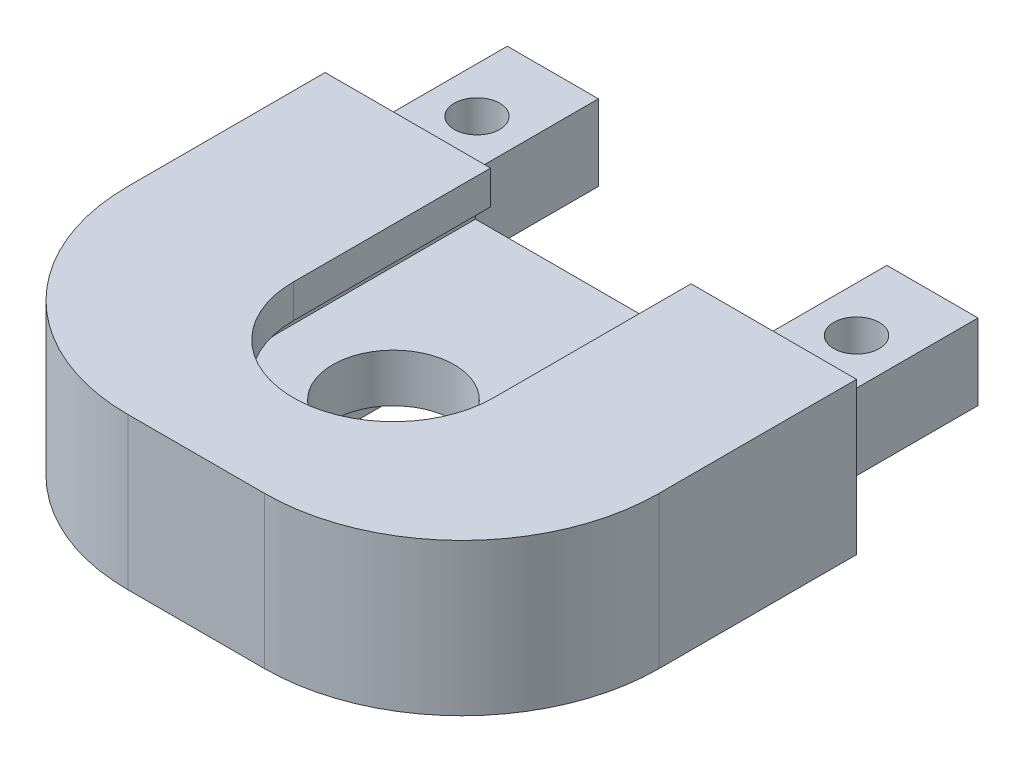
SolidWorks part; units mm, degrees
ref_plane "Front Plane" through (0, 0, 0) normal (0, 0, 1) x (1, 0, 0)
ref_plane "Top Plane" through (0, 0, 0) normal (0, 1, 0) x (1, 0, 0)
ref_plane "Right Plane" through (0, 0, 0) normal (1, 0, 0) x (0, 0, -1)
sketch "Sketch1" plane through (0, 0, 0) normal (0, 1, 0) x (1, 0, 0)
  line L0 (0, 0) -> (6, 0)
  line L1 (6, 0) -> (6, -10)
  line L2 (6, -10) -> (25, -10)
  line L3 (25, -10) -> (25, 0)
  line L4 (25, 0) -> (31, 0)
  line L5 (31, 0) -> (31, -10)
  line L7 (0, -10) -> (0, 0)
  line L8 (0, -10) -> (-2, -10)
  line L11 (33, -36) -> (33, -10)
  line L12 (33, -10) -> (31, -10)
  line L13 (3, 0) -> (3, -5) construction
  line L14 (15.5, -10) -> (15.5, 0) construction
  line L15 (33, -36) -> (-2, -36)
  line L16 (-2, -36) -> (-2, -10)
  circle A0 centre (3, -5) radius 1.5
  circle A1 centre (28, -5) radius 1.5
  dimension "D9" = 3
  dimension "D1" = 36
  dimension "D2" = 35
  dimension "D3" = 10
  dimension "D4" = 6
  dimension "D5" = 2
  dimension "D6" = 6
  dimension "D7" = 2
  dimension "D8" = 5
extrude "Boss-Extrude1" add sketch "Sketch1" along normal blind 5
sketch "Sketch2" plane through (0, 0, 36) normal (0, 0, 1) x (1, 0, 0)
  line L0 (-2, 5) -> (-2, 7.5)
  line L1 (-2, 7.5) -> (33, 7.5)
  line L2 (33, 7.5) -> (33, 5)
  line L3 (33, 5) -> (-2, 5)
  line L4 (-2, 0) -> (33, 0)
  line L5 (33, 0) -> (33, -2.5)
  line L6 (33, -2.5) -> (-2, -2.5)
  line L7 (-2, -2.5) -> (-2, 0)
  dimension "D1" = 10
extrude "Boss-Extrude2" add sketch "Sketch2" against normal up to surface (26 mm away) up to face at (15.5, 2.5, 10)
fillet "Fillet1" radius 13 2 edges at (33, 2.5, 36) (-2, 2.5, 36)
ref_plane "Plane1" through (0, 2.5, 0) normal (0, -1, 0) x (-1, 0, 0)
sketch "Sketch3" plane through (0, 0, 10) normal (0, 0, -1) x (-1, 0, 0)
  line L0 (-22.1, 7.5) -> (-22.1, 5.2875)
  line L1 (2, 7.5) -> (-33, 7.5) construction
  line L2 (-22.1, 5.2875) -> (-23.1, 5.2875)
  line L3 (-23.1, 5.2875) -> (-23.1, 4.0875)
  line L4 (-23.1, 4.0875) -> (-15.5, 4.0875)
  line L5 (-15.5, 4.0875) -> (-7.9, 4.0875)
  line L6 (-7.9, 4.0875) -> (-7.9, 5.2875)
  line L7 (-7.9, 5.2875) -> (-8.9, 5.2875)
  line L8 (-8.9, 5.2875) -> (-8.9, 7.5)
  line L9 (-8.9, 7.5) -> (-22.1, 7.5)
  line L10 (-25, 2.5) -> (-6, 2.5) construction
  line L11 (-25, 5) -> (-25, 0) construction
  line L12 (-6, 5) -> (-6, 0) construction
  line L13 (-15.5, 2.5) -> (-15.5, 4.0875) construction
  dimension "D1" = 1.2
  dimension "D2" = 3.4125
  dimension "D3" = 13.2
  dimension "D4" = 15.2
extrude "Cut-Extrude1" cut sketch "Sketch3" against normal blind 13 and the other way through all
sketch "Sketch4" plane through (0, 4.0875, 0) normal (0, 1, 0) x (1, 0, 0)
  line L0 (8.9, -23) -> (22.1, -23) construction
  circle A0 centre (15.5, -23) radius 7.6
  dimension "D1" = 15.2
extrude "Cut-Extrude2" cut sketch "Sketch4" along normal up to surface (1.2 mm away) up to face at (8.4, 5.2875, 16.5)
sketch "Sketch5" plane through (0, 4.0875, 0) normal (0, 1, 0) x (1, 0, 0)
  line L0 (8.9, -23) -> (22.1, -23) construction
  circle A0 centre (15.5, -23) radius 6.6
  dimension "D1" = 13.2
extrude "Cut-Extrude3" cut sketch "Sketch5" along normal through all
mirror "Mirror1" about plane through (0, 2.5, 0) normal (0, -1, 0) of "Cut-Extrude1"
sketch "Sketch6" plane through (0, 0.9125, 0) normal (0, -1, 0) x (1, 0, 0)
  line L0 (8.9, 23) -> (22.1, 23) construction
  circle A0 centre (15.5, 23) radius 7.6
  dimension "D1" = 15.2
extrude "Cut-Extrude4" cut sketch "Sketch6" along normal up to surface (1.2 mm away) up to face at (8.4, -0.2875, 16.5)
sketch "Sketch7" plane through (0, 0.9125, 0) normal (0, -1, 0) x (1, 0, 0)
  line L0 (8.9, 23) -> (22.1, 23) construction
  circle A0 centre (15.5, 23) radius 6.6
  dimension "D1" = 13.2
extrude "Cut-Extrude5" cut sketch "Sketch7" along normal through all
sketch "Sketch8" plane through (0, 4.0875, 0) normal (0, 1, 0) x (1, 0, 0)
  circle A0 centre (15.5, -23) radius 4
  dimension "D1" = 8
extrude "Cut-Extrude6" cut sketch "Sketch8" against normal through all
